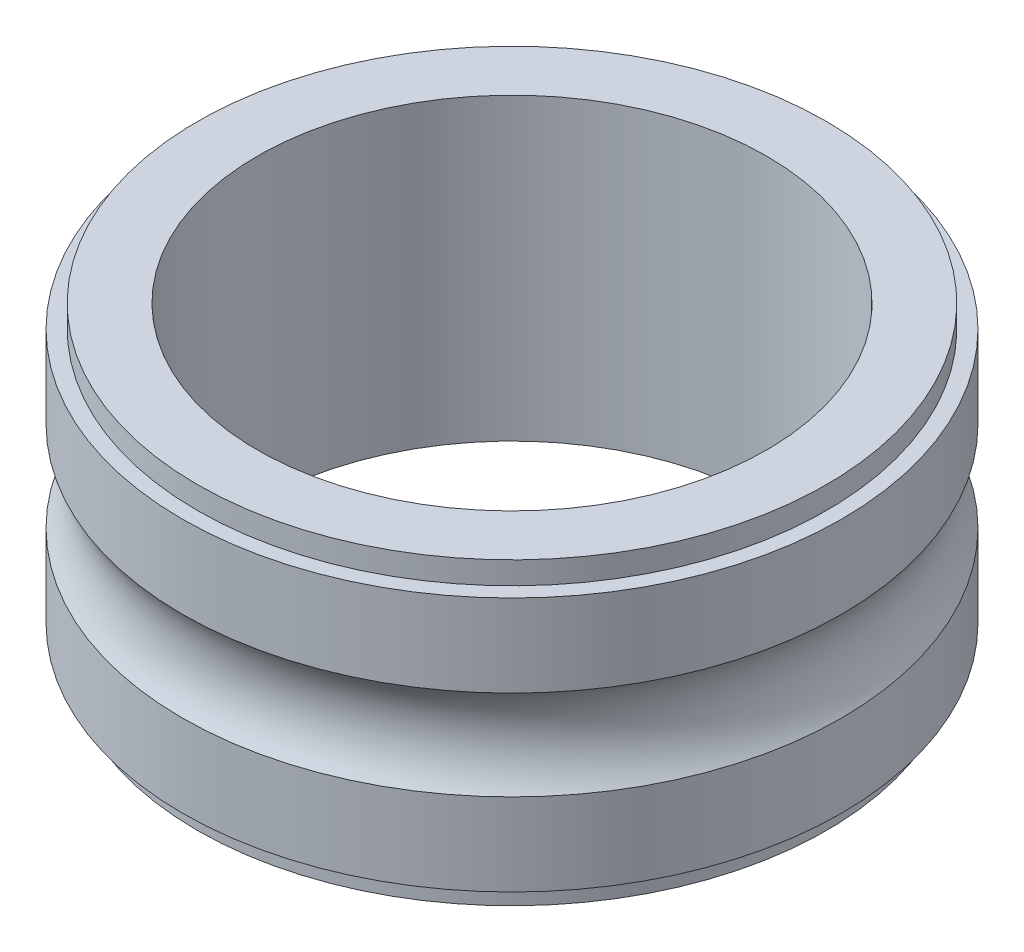
SolidWorks part; units mm, degrees
ref_plane "Front Plane" through (0, 0, 0) normal (0, 0, 1) x (1, 0, 0)
ref_plane "Top Plane" through (0, 0, 0) normal (0, 1, 0) x (1, 0, 0)
ref_plane "Right Plane" through (0, 0, 0) normal (1, 0, 0) x (0, 0, -1)
sketch "Sketch1" plane through (0, 0, 0) normal (0, 0, 1) x (1, 0, 0)
  line L0 (0, 0) -> (12429.4001, 0) construction
  line L1 (0, 0) -> (0, 12429.4001) construction
  line L2 (11, 4.25) -> (11, 1.5)
  line L3 (8.5, -5) -> (10.5, -5)
  line L4 (8.5, -5) -> (8.5, 5)
  line L5 (8.5, 5) -> (10.5, 5)
  line L6 (13, -5) -> (13, 5) construction
  line L7 (8.5, -5) -> (13, 5) construction
  line L8 (8.5, 5) -> (13, -5) construction
  line L9 (11, 5) -> (13, 5) construction
  line L10 (11, -5) -> (13, -5) construction
  line L11 (11, 1.5) -> (11, 0) construction
  line L12 (11, -1.5) -> (11, -4.25)
  line L13 (11, 0) -> (11, -1.5) construction
  line L14 (10.5, 5) -> (10.5, 4.25)
  line L15 (10.5, 4.25) -> (11, 4.25)
  line L16 (10.5, -4.25) -> (11, -4.25)
  line L17 (10.5, -5) -> (10.5, -4.25)
  line L18 (10.5, 5) -> (11, 5) construction
  line L19 (11, 5) -> (11, 4.25) construction
  line L20 (11, -4.25) -> (11, -5) construction
  line L21 (10.5, -5) -> (11, -5) construction
  arc A0 (11, 1.5) -> (11, -1.5) centre (13, 0) ccw
  arc A1 (13, -2.5) -> (15.5, 0) centre (13, 0) ccw construction
  arc A2 (15.5, 0) -> (13, 2.5) centre (13, 0) ccw construction
  arc A3 (13, 2.5) -> (11, 1.5) centre (13, 0) ccw construction
  arc A4 (11, -1.5) -> (13, -2.5) centre (13, 0) ccw construction
  point P5 (10.75, 0)
  dimension "D4" = 5
  dimension "D1" = 8.5
  dimension "D2" = 4.5
  dimension "D3" = 10
  dimension "D5" = 2
  dimension "D6" = 0.5
  dimension "D7" = 0.75
revolve "Revolve2" add sketch "Sketch1" angle 360 about L1
